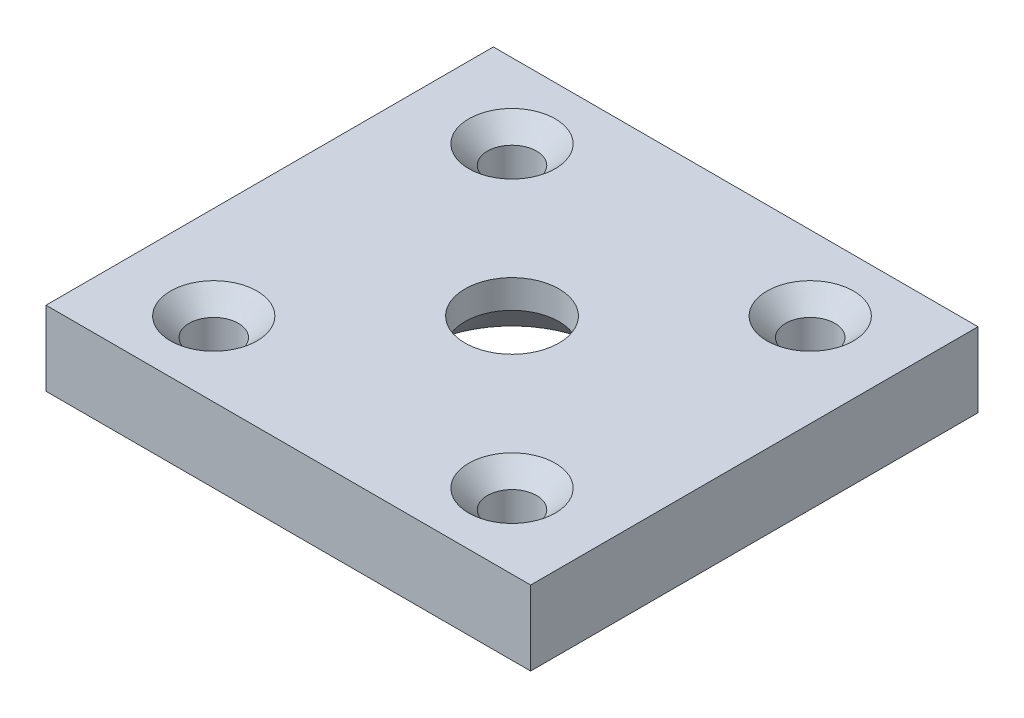
SolidWorks part; units mm, degrees
ref_plane "Front Plane" through (0, 0, 0) normal (0, 0, 1) x (1, 0, 0)
ref_plane "Top Plane" through (0, 0, 0) normal (0, 1, 0) x (1, 0, 0)
ref_plane "Right Plane" through (0, 0, 0) normal (1, 0, 0) x (0, 0, -1)
sketch "Sketch1" plane through (0, 0, 0) normal (0, 1, 0) x (1, 0, 0)
  line L1 (-16.25, -15) -> (16.25, -15)
  line L2 (-16.25, -15) -> (-16.25, 15)
  line L3 (-16.25, 15) -> (16.25, 15)
  line L4 (16.25, -15) -> (16.25, 15)
  line L5 (-16.25, -15) -> (16.25, 15) construction
  line L6 (-16.25, 15) -> (16.25, -15) construction
  line L7 (-10, 10) -> (10, 10) construction
  line L8 (-10, 10) -> (-10, -10) construction
  line L9 (-10, -10) -> (10, -10) construction
  line L10 (10, 10) -> (10, -10) construction
  line L11 (-10, 10) -> (10, -10) construction
  line L12 (-10, -10) -> (10, 10) construction
  point P0 (0, 0)
  point P5 (0, 0)
extrude "Boss-Extrude1" add sketch "Sketch1" along normal blind 5
hole_wizard "CSK for M6 Hex Socket Countersunk Cap Screw1" positions "Sketch2" profile "Sketch3" countersink size "M6" standard "ISO" end condition through all
sketch "Sketch2" plane through (0, 0, 0) normal (0, -1, 0) x (-1, 0, 0)
  point P0 (0, 0)
sketch "Sketch3" plane through (0, 0, 0) normal (1, 0, 0) x (0, 0, -1)
  line L0 (0, 0) -> (0, 5)
  line L1 (0, 5) -> (3.15, 5)
  line L2 (3.15, 5) -> (3.15, 3.1)
  line L3 (3.15, 3.1) -> (6.25, 0)
  line L5 (6.25, 0) -> (0, 0)
  line L6 (-3.15, 3.1) -> (-6.25, 0) construction
  line L11 (0, -6.35) -> (0, 107.95) construction
  dimension "Thru Hole Dia." = 6.3
  dimension "Thru Hole Depth" = 5
  dimension "Near C'Sink Dia." = 12.5
  dimension "Near C'Sink Angle" = 90
hole_wizard "CSK for M3 Countersunk Flat Head Screw1" positions "Sketch6" profile "Sketch7" countersink size "M3" standard "ISO" end condition through all
sketch "Sketch6" plane through (0, 5, 0) normal (0, 1, 0) x (1, 0, 0)
  line L1 (-10, 10) -> (10, 10)
  line L2 (-10, 10) -> (-10, -10)
  line L3 (-10, -10) -> (10, -10)
  line L4 (10, 10) -> (10, -10)
  line L5 (-10, 10) -> (10, -10) construction
  line L6 (-10, -10) -> (10, 10) construction
  point P1 (0, 0)
  point P2 (10, -10)
  point P5 (-10, 10)
  point P6 (-10, -10)
  point P7 (10, 10)
sketch "Sketch7" plane through (0, 5, 0) normal (1, 0, 0) x (0, 0, 1)
  line L0 (0, 0) -> (0, 5)
  line L1 (0, 5) -> (1.65, 5)
  line L2 (1.65, 5) -> (1.65, 1.25)
  line L3 (1.65, 1.25) -> (2.9, 0)
  line L5 (2.9, 0) -> (0, 0)
  line L6 (-1.65, 1.25) -> (-2.9, 0) construction
  line L11 (0, -6.35) -> (0, 107.95) construction
  dimension "Thru Hole Dia." = 3.3
  dimension "Thru Hole Depth" = 5
  dimension "Near C'Sink Dia." = 5.8
  dimension "Near C'Sink Angle" = 90
